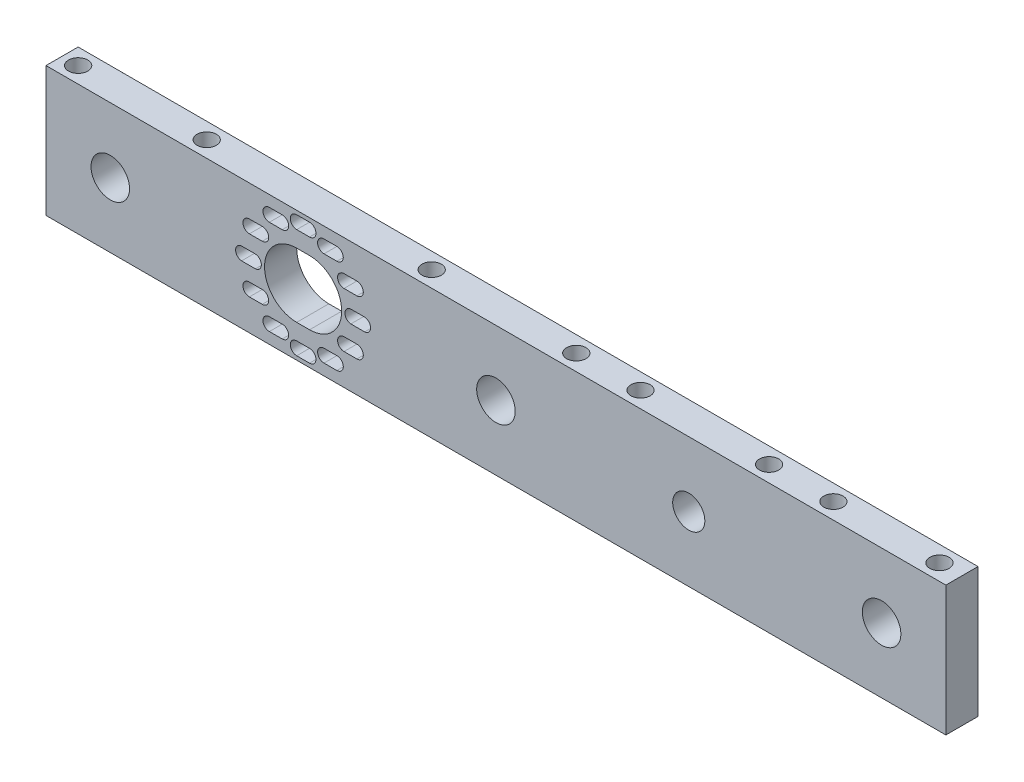
SolidWorks part; units mm, degrees
ref_plane "정면" through (0, 0, 0) normal (0, 0, 1) x (1, 0, 0)
ref_plane "윗면" through (0, 0, 0) normal (0, 1, 0) x (1, 0, 0)
ref_plane "우측면" through (0, 0, 0) normal (1, 0, 0) x (0, 0, -1)
sketch "스케치1" plane through (0, 0, 0) normal (0, 0, 1) x (1, 0, 0)
  line L0 (0, 0) -> (-17.0444, 0) construction
  line L1 (-17.0444, 0) -> (-13.1261, 0.8046) construction
  line L2 (0, 3.5) -> (0, 0) construction
  line L3 (-13.1261, 0.8046) -> (0, 3.5) construction
  line L4 (-16.0444, 5) -> (-18.0444, 5)
  line L5 (-16.0444, -5) -> (-18.0444, -5)
  line L6 (-57.046, -10.1) -> (-57.046, 10.1)
  line L7 (-57.046, 10.1) -> (82.954, 10.1)
  line L8 (0, 0) -> (0, -10.1) construction
  line L9 (-16.0444, 7.5) -> (-18.0444, 7.5)
  line L10 (-16.0444, 9.5) -> (-18.0444, 9.5)
  line L11 (-10.6831, -5.25) -> (-8.6831, -5.25)
  line L12 (8, -10.1) -> (-30.75, -10.1) construction
  line L13 (-9.6207, -1) -> (-7.468, -1)
  line L14 (-9.5444, 1) -> (-7.5444, 1)
  line L15 (-20.2944, 8.3612) -> (-22.2944, 8.3612)
  line L16 (-20.2944, 6.3612) -> (-22.2944, 6.3612)
  line L17 (-23.4056, 5.25) -> (-25.4056, 5.25)
  line L18 (-23.4056, 3.25) -> (-25.4056, 3.25)
  line L19 (-24.5444, 1) -> (-26.5444, 1)
  line L20 (-24.468, -1) -> (-26.6207, -1)
  line L21 (-10.6831, 3.25) -> (-8.6831, 3.25)
  line L22 (-10.6831, 5.25) -> (-8.6831, 5.25)
  line L23 (-13.7944, 6.3612) -> (-11.7944, 6.3612)
  line L24 (-13.7944, 8.3612) -> (-11.7944, 8.3612)
  line L25 (-10.6831, -3.25) -> (-8.6831, -3.25)
  line L26 (-23.4056, -3.25) -> (-25.4056, -3.25)
  line L27 (-23.4056, -5.25) -> (-25.4056, -5.25)
  line L28 (-13.7944, -8.3612) -> (-11.7944, -8.3612)
  line L29 (-13.7944, -6.3612) -> (-11.7944, -6.3612)
  line L30 (-20.2944, -6.3612) -> (-22.2944, -6.3612)
  line L31 (-20.2944, -8.3612) -> (-22.2944, -8.3612)
  line L32 (-16.0444, -9.5) -> (-18.0444, -9.5)
  line L33 (-16.0444, -7.5) -> (-18.0444, -7.5)
  line L34 (42.954, 0) -> (72.954, 0) construction
  line L35 (12.9556, 0) -> (42.954, 0) construction
  line L36 (-57.046, -10.1) -> (82.954, -10.1)
  line L37 (-47.0444, 0) -> (-57.046, 0) construction
  line L38 (72.954, 0) -> (82.954, 0) construction
  line L42 (82.954, -10.1) -> (82.954, 10.1)
  line L64 (-17.0444, -12.5) -> (-17.0444, -10.1) construction
  circle A0 centre (-17.0444, 0) radius 30 construction
  circle A1 centre (12.9556, 0) radius 20 construction
  circle A2 centre (-47.0444, 0) radius 3
  circle A3 centre (12.9556, 0) radius 3
  circle A4 centre (42.954, 0) radius 9.9983 construction
  circle A5 centre (42.954, 0) radius 2.5
  circle A6 centre (-17.0444, 0) radius 4 construction
  circle A7 centre (-17.0444, 0) radius 4.4 construction
  circle A8 centre (-17.0444, 0) radius 5 construction
  arc A9 (-18.0444, 5) -> (-18.0444, -5) centre (-18.0444, 0) ccw
  arc A10 (-16.0444, 5) -> (-16.0444, -5) centre (-16.0444, 0) cw
  circle A11 centre (-17.0444, 0) radius 12.5 construction
  circle A12 centre (-17.0444, 0) radius 8.5 construction
  circle A13 centre (-17.0444, 8.5) radius 1 construction
  arc A14 (-18.0444, 9.5) -> (-18.0444, 7.5) centre (-18.0444, 8.5) ccw
  arc A15 (-16.0444, 9.5) -> (-16.0444, 7.5) centre (-16.0444, 8.5) cw
  circle A16 centre (-21.2944, 7.3612) radius 1 construction
  circle A17 centre (-24.4056, 4.25) radius 1 construction
  circle A18 centre (-25.5444, 0) radius 1 construction
  arc A19 (-25.4056, 5.25) -> (-25.4056, 3.25) centre (-25.4056, 4.25) ccw
  arc A20 (-26.5444, 1) -> (-26.6207, -1) centre (-26.5444, -0.0015) ccw
  arc A21 (-23.4056, 5.25) -> (-23.4056, 3.25) centre (-23.4056, 4.25) cw
  arc A22 (-24.5444, 1) -> (-24.468, -1) centre (-24.5444, -0.0015) cw
  arc A23 (-22.2944, 8.3612) -> (-22.2944, 6.3612) centre (-22.2944, 7.3612) ccw
  arc A24 (-20.2944, 8.3612) -> (-20.2944, 6.3612) centre (-20.2944, 7.3612) cw
  circle A25 centre (-8.5444, 0) radius 1 construction
  arc A26 (-9.5444, 1) -> (-9.6207, -1) centre (-9.5444, -0.0015) ccw
  arc A27 (-7.5444, 1) -> (-7.468, -1) centre (-7.5444, -0.0015) cw
  circle A28 centre (-9.6831, 4.25) radius 1 construction
  arc A29 (-10.6831, 5.25) -> (-10.6831, 3.25) centre (-10.6831, 4.25) ccw
  arc A30 (-8.6831, 5.25) -> (-8.6831, 3.25) centre (-8.6831, 4.25) cw
  circle A31 centre (-12.7944, 7.3612) radius 1 construction
  arc A32 (-13.7944, 8.3612) -> (-13.7944, 6.3612) centre (-13.7944, 7.3612) ccw
  arc A33 (-11.7944, 8.3612) -> (-11.7944, 6.3612) centre (-11.7944, 7.3612) cw
  arc A34 (-10.6831, -5.25) -> (-10.6831, -3.25) centre (-10.6831, -4.25) cw
  circle A35 centre (-9.6831, -4.25) radius 1 construction
  arc A36 (-8.6831, -5.25) -> (-8.6831, -3.25) centre (-8.6831, -4.25) ccw
  circle A37 centre (-24.4056, -4.25) radius 1 construction
  arc A38 (-23.4056, -5.25) -> (-23.4056, -3.25) centre (-23.4056, -4.25) ccw
  arc A39 (-25.4056, -5.25) -> (-25.4056, -3.25) centre (-25.4056, -4.25) cw
  arc A40 (-22.2944, -8.3612) -> (-22.2944, -6.3612) centre (-22.2944, -7.3612) cw
  circle A41 centre (-12.7944, -7.3612) radius 1 construction
  circle A42 centre (-21.2944, -7.3612) radius 1 construction
  circle A43 centre (-17.0444, -8.5) radius 1 construction
  arc A44 (-11.7944, -8.3612) -> (-11.7944, -6.3612) centre (-11.7944, -7.3612) ccw
  arc A45 (-13.7944, -8.3612) -> (-13.7944, -6.3612) centre (-13.7944, -7.3612) cw
  arc A46 (-20.2944, -8.3612) -> (-20.2944, -6.3612) centre (-20.2944, -7.3612) ccw
  arc A47 (-16.0444, -9.5) -> (-16.0444, -7.5) centre (-16.0444, -8.5) ccw
  arc A48 (-18.0444, -9.5) -> (-18.0444, -7.5) centre (-18.0444, -8.5) cw
  circle A49 centre (72.954, 0) radius 3
  circle A50 centre (72.954, 0) radius 20.0017 construction
  circle A52 centre (-17.0444, 0) radius 11 construction
  dimension "D4" = 30
  dimension "D5" = 29.9983
  dimension "D6" = 30
  dimension "D7" = 30
  dimension "D8" = 8
  dimension "D9" = 8.8
  dimension "D10" = 10
  dimension "D11" = 140
  dimension "D12" = 25
  dimension "D14" = 10.0017
  dimension "D13" = 17
  dimension "D16" = 6
  dimension "D17" = 5
  dimension "D19" = 6
  dimension "D20" = 6
  dimension "D21" = 20.2
  dimension "D2" = 13.4
  dimension "D3" = 3.5
  dimension "D15" = 10
  dimension "D18" = 2.4
extrude "돌출1" add sketch "스케치1" along normal blind 5
sketch "스케치5" plane through (0, 0, 5) normal (0, 0, 1) x (1, 0, 0)
  line L0 (-17.0444, -5) -> (-17.0444, 5)
  line L1 (-18.0444, -5) -> (-16.0444, -5) construction
  line L2 (-16.0444, 5) -> (-18.0444, 5) construction
  line L3 (-17.0444, 5) -> (-23.0444, 0)
  line L4 (-23.0444, 0) -> (-17.0444, -5)
  line L5 (-17.0444, 0) -> (-23.0444, 0)
  arc A0 (-18.0444, 5) -> (-18.0444, -5) centre (-18.0444, 0) ccw construction
  circle A1 centre (-17.0444, 0) radius 12.5
  dimension "D1" = 25
sketch "스케치6" plane through (0, 0, 0) normal (0, 0, -1) x (-1, 0, 0)
  line L0 (17.0444, -5) -> (17.0444, 5) construction
  circle A0 centre (17.0444, 0) radius 12.5
  circle A1 centre (17.0444, 0) radius 12.5 construction
sketch "스케치7" plane through (0, 0, 0) normal (0, 0, -1) x (-1, 0, 0)
  line L0 (17.0444, -5) -> (17.0444, 5)
  line L1 (17.0444, -5) -> (17.0444, 5) construction
  line L2 (23.0444, 0) -> (17.0444, -5) construction
  line L3 (16.0444, 5) -> (18.0444, 5) construction
  line L4 (57.046, -10.1) -> (57.046, 10.1)
sketch "스케치10" plane through (0, 0, 5) normal (0, 0, 1) x (1, 0, 0)
  line L0 (72.954, 0) -> (82.954, 0)
  line L1 (82.954, -10.1) -> (82.954, 10.1) construction
  line L2 (42.954, 0) -> (72.954, 0)
  line L3 (12.9556, 0) -> (42.954, 0)
  line L4 (12.9556, 0) -> (-17.0444, 0)
  line L5 (-17.0444, 0) -> (-47.0444, 0)
  line L6 (-47.0444, 0) -> (-57.046, 0)
  line L7 (-57.046, 10.1) -> (-57.046, -10.1) construction
sketch "스케치8" plane through (0, -10.1, 0) normal (0, -1, 0) x (1, 0, 0)
  line L0 (82.954, 2.5) -> (-57.046, 2.5)
  line L1 (82.954, 5) -> (82.954, 0) construction
  line L2 (-57.046, 5) -> (-57.046, 0) construction
  circle A0 centre (-54.5444, 2.5) radius 1.5
  circle A1 centre (-34.5444, 2.5) radius 1.5
  circle A2 centre (0.4556, 2.5) radius 1.5
  circle A3 centre (32.954, 2.5) radius 1.5
  circle A4 centre (22.954, 2.5) radius 1.5
  circle A5 centre (52.954, 2.5) radius 1.5
  circle A6 centre (62.954, 2.5) radius 1.5
  circle A7 centre (79.454, 2.5) radius 1.5
  dimension "D1" = 3
  dimension "D4" = 10
  dimension "D5" = 10
  dimension "D6" = 10
  dimension "D8" = 35
  dimension "D9" = 20
  dimension "D2" = 3.5
  dimension "D3" = 10
  dimension "D7" = 12.5
extrude "컷-돌출1" cut sketch "스케치8" against normal blind 41 contours L0 A7 | L0 A7 | L0 A6 | L0 A6 | L0 A5 | L0 A5 | L0 A3 | L0 A3 | L0 A4 | L0 A4 | L0 A2 | L0 A2 | L0 A1 | L0 A1 | L0 A0 | L0 A0
